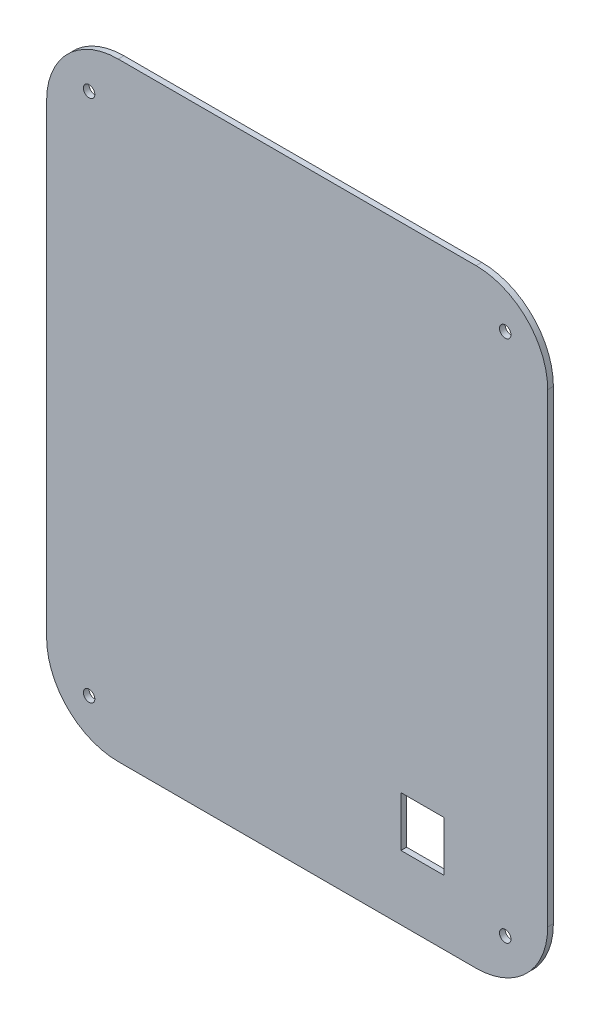
SolidWorks part; units mm, degrees
material "Acrylic (Medium-high impact)"
ref_plane "Front Plane" through (0, 0, 0) normal (0, 0, 1) x (1, 0, 0)
ref_plane "Top Plane" through (0, 0, 0) normal (0, 1, 0) x (1, 0, 0)
ref_plane "Right Plane" through (0, 0, 0) normal (1, 0, 0) x (0, 0, -1)
sketch "Sketch1" plane through (0, 0, 0) normal (0, 0, 1) x (1, 0, 0)
  line L0 (52.8773, 101.0393) -> (-47.1227, 101.0393) construction
  line L1 (72.8773, -48.9607) -> (72.8773, 81.0393) construction
  line L2 (-47.1227, -68.9607) -> (52.8773, -68.9607) construction
  line L3 (-67.1227, 81.0393) -> (-67.1227, -48.9607) construction
  line L4 (52.8773, 101.0393) -> (-47.1227, 101.0393)
  line L5 (72.8773, -48.9607) -> (72.8773, 81.0393)
  line L6 (-47.1227, -68.9607) -> (52.8773, -68.9607)
  line L7 (-67.1227, 81.0393) -> (-67.1227, -48.9607)
  arc A0 (72.8773, 81.0393) -> (52.8773, 101.0393) centre (52.8773, 81.0393) ccw construction
  arc A1 (52.8773, -68.9607) -> (72.8773, -48.9607) centre (52.8773, -48.9607) ccw construction
  arc A2 (-67.1227, -48.9607) -> (-47.1227, -68.9607) centre (-47.1227, -48.9607) ccw construction
  arc A3 (-47.1227, 101.0393) -> (-67.1227, 81.0393) centre (-47.1227, 81.0393) ccw construction
  arc A4 (72.8773, 81.0393) -> (52.8773, 101.0393) centre (52.8773, 81.0393) ccw
  arc A5 (52.8773, -68.9607) -> (72.8773, -48.9607) centre (52.8773, -48.9607) ccw
  arc A6 (-67.1227, -48.9607) -> (-47.1227, -68.9607) centre (-47.1227, -48.9607) ccw
  arc A7 (-47.1227, 101.0393) -> (-67.1227, 81.0393) centre (-47.1227, 81.0393) ccw
  circle A8 centre (-55.2544, -57.0924) radius 1.6 construction
  circle A9 centre (61.009, -57.0924) radius 1.6 construction
  circle A10 centre (61.009, 89.1711) radius 1.6 construction
  circle A11 centre (-55.2544, 89.1711) radius 1.6 construction
  circle A12 centre (-55.2544, -57.0924) radius 1.6
  circle A13 centre (61.009, -57.0924) radius 1.6
  circle A14 centre (61.009, 89.1711) radius 1.6
  circle A15 centre (-55.2544, 89.1711) radius 1.6
extrude "Boss-Extrude1" add sketch "Sketch1" along normal blind 1.5875
sketch "Sketch3" plane through (0, 0, 1.5875) normal (0, 0, 1) x (1, 0, 0)
  line L0 (31.8773, -52.4607) -> (43.8773, -52.4607) construction
  line L1 (31.8773, -37.4607) -> (31.8773, -52.4607) construction
  line L3 (43.8773, -37.4607) -> (43.8773, -52.4607) construction
  line L4 (31.8773, -52.4607) -> (43.8773, -52.4607)
  line L5 (31.8773, -36.9607) -> (31.8773, -52.4607)
  line L7 (43.8773, -36.9607) -> (43.8773, -52.4607)
  line L9 (43.8773, -36.9607) -> (31.8773, -36.9607)
  line L10 (31.8773, -50.9607) -> (43.8773, -50.9607)
  dimension "D1" = 14
  dimension "D2" = 1.5
extrude "Cut-Extrude1" cut sketch "Sketch3" against normal through all contours L5 L10 L7 L9
